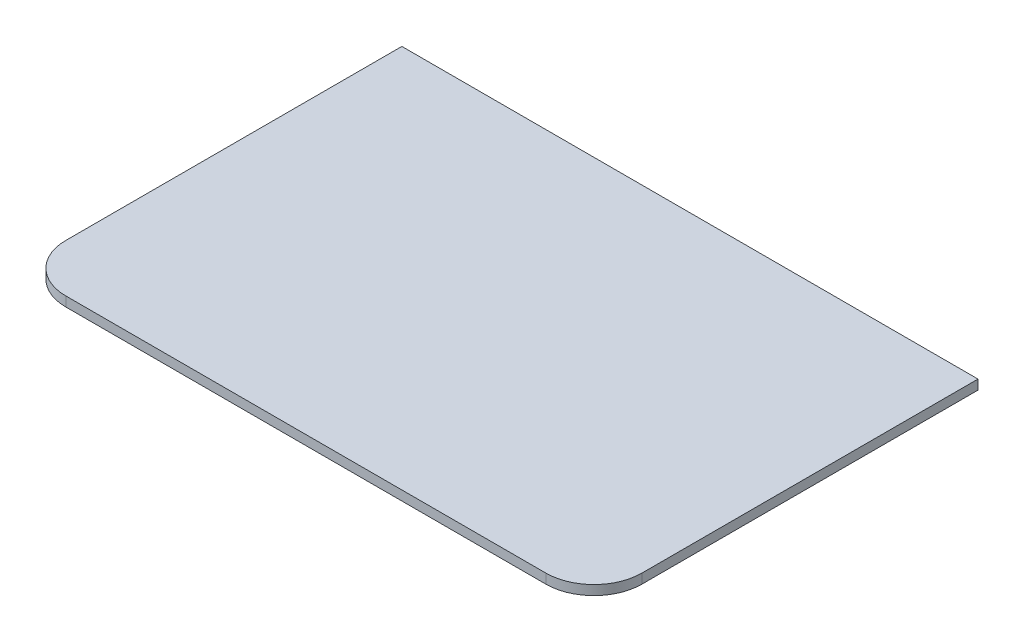
SolidWorks part; units mm, degrees
ref_plane "Front Plane" through (0, 0, 0) normal (0, 0, 1) x (1, 0, 0)
ref_plane "Top Plane" through (0, 0, 0) normal (0, 1, 0) x (1, 0, 0)
ref_plane "Right Plane" through (0, 0, 0) normal (1, 0, 0) x (0, 0, -1)
sketch "Sketch1" plane through (0, 0, 0) normal (0, 1, 0) x (1, 0, 0)
  line L1 (-60, 40) -> (60, 40)
  line L2 (-60, 40) -> (-60, -40)
  line L3 (-60, -40) -> (60, -40)
  line L4 (60, 40) -> (60, -40)
  line L5 (-60, 40) -> (60, -40) construction
  line L6 (-60, -40) -> (60, 40) construction
  point P0 (0, 0)
extrude "Boss-Extrude1" add sketch "Sketch1" along normal blind 2
fillet "Fillet1" radius 10 2 edges at (60, 1, 40) (-60, 1, 40)
